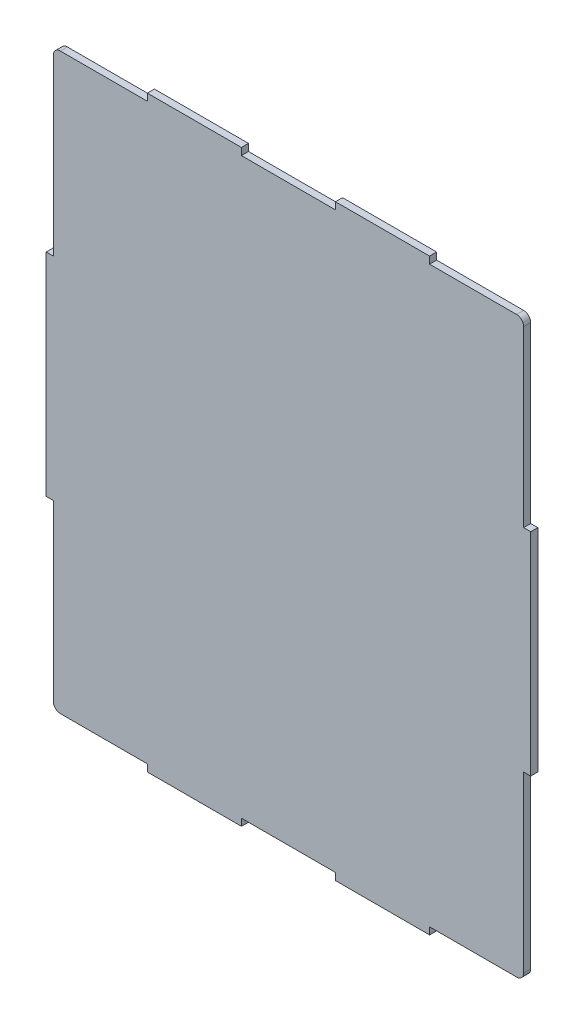
SolidWorks part; units mm, degrees
ref_plane "Front Plane" through (0, 0, 0) normal (0, 0, 1) x (1, 0, 0)
ref_plane "Top Plane" through (0, 0, 0) normal (0, 1, 0) x (1, 0, 0)
ref_plane "Right Plane" through (0, 0, 0) normal (1, 0, 0) x (0, 0, -1)
sketch "Sketch1" plane through (0, 0, 0) normal (0, 0, 1) x (1, 0, 0)
  line L0 (100, 45) -> (103, 45)
  line L1 (97, 122) -> (-97, 122)
  line L2 (100, 119) -> (100, -119)
  line L3 (97, -122) -> (-97, -122)
  line L4 (-100, 119) -> (-100, -119)
  line L5 (100, 122) -> (-100, -122) construction
  line L6 (100, -122) -> (-100, 122) construction
  line L7 (103, 45) -> (103, -45)
  line L8 (103, -45) -> (100, -45)
  line L9 (-100, 45) -> (-103, 45)
  line L10 (-103, 45) -> (-103, -45)
  line L11 (-103, -45) -> (-100, -45)
  line L12 (-60, 122) -> (-60, 125)
  line L13 (-60, 125) -> (-20, 125)
  line L14 (-20, 125) -> (-20, 122)
  line L15 (20, 122) -> (20, 125)
  line L16 (20, 125) -> (60, 125)
  line L17 (60, 125) -> (60, 122)
  line L18 (-60, -122) -> (-60, -125)
  line L19 (-60, -125) -> (-20, -125)
  line L20 (-20, -125) -> (-20, -122)
  line L21 (20, -122) -> (20, -125)
  line L22 (20, -125) -> (60, -125)
  line L23 (60, -125) -> (60, -122)
  arc A0 (100, -119) -> (97, -122) centre (97, -119) cw
  arc A1 (-97, -122) -> (-100, -119) centre (-97, -119) cw
  arc A2 (97, 122) -> (100, 119) centre (97, 119) cw
  arc A3 (-97, 122) -> (-100, 119) centre (-97, 119) ccw
  point P0 (0, 0)
  dimension "D8" = 3
  dimension "D1" = 200
  dimension "D2" = 244
  dimension "D3" = 3
  dimension "D4" = 3
  dimension "D5" = 90
  dimension "D6" = 90
  dimension "D7" = 77
  dimension "D9" = 40
  dimension "D10" = 40
  dimension "D11" = 40
  dimension "D12" = 40
  dimension "D13" = 3
  dimension "D14" = 3
  dimension "D15" = 40
  dimension "D16" = 40
  dimension "D17" = 40
  dimension "D18" = 40
  dimension "D19" = 3
  dimension "D20" = 3
extrude "Boss-Extrude1" add sketch "Sketch1" along normal blind 3 contours L1 A3 L4 A1 L3 A0 L2 A2 | L14 L13 L12 L1 | L17 L16 L15 L1 | L10 L11 L4 L9 | L8 L7 L0 L2 | L22 L23 L3 L21 | L19 L20 L3 L18
